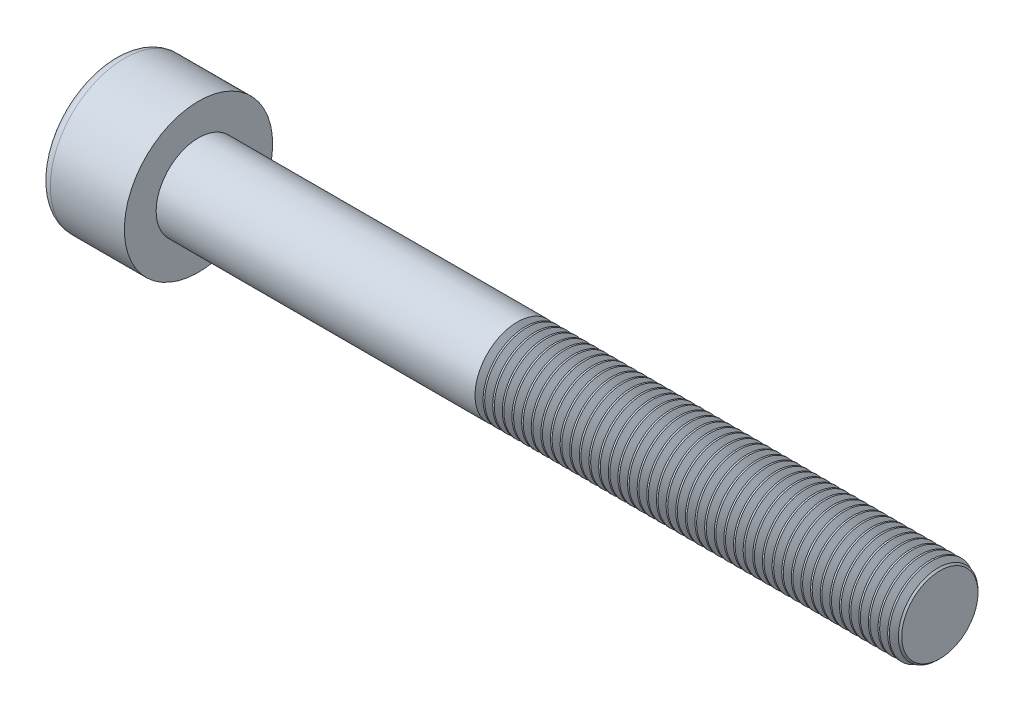
SolidWorks part; units mm, degrees
ref_plane "Front" through (0, 0, 0) normal (0, 0, 1) x (1, 0, 0)
ref_plane "Top" through (0, 0, 0) normal (0, 1, 0) x (1, 0, 0)
ref_plane "Right" through (0, 0, 0) normal (1, 0, 0) x (0, 0, -1)
sketch "Sketch1" plane through (0, 0, 0) normal (1, 0, 0) x (0, 0, -1)
  circle A0 centre (0, 0) radius 3.5
  dimension "dk" = 7
extrude "BaseHead" add sketch "Sketch1" along normal blind 4
sketch "Sketch2" plane through (4, 0, 0) normal (1, 0, 0) x (0, 0, -1)
  circle A0 centre (0, 0) radius 2
  dimension "d" = 4
extrude "BaseBody" add sketch "Sketch2" along normal blind 35
cosmetic thread "ThreadCosmetic1" [suppressed] parameters "b"=20, "D2"=3.242
sketch "Sketch3" plane through (0, 0, 0) normal (1, 0, 0) x (0, 0, -1)
  line L1 (1.7321, 0) -> (0.866, 1.5)
  line L2 (0.866, 1.5) -> (-0.866, 1.5)
  line L3 (-0.866, 1.5) -> (-1.7321, 0)
  line L4 (-1.7321, 0) -> (-0.866, -1.5)
  line L5 (-0.866, -1.5) -> (0.866, -1.5)
  line L6 (0.866, -1.5) -> (1.7321, 0)
  circle A0 centre (0, 0) radius 1.5 construction
  dimension "s" = 3
  dimension "e" = 3.4641
extrude "HexagonSocket" cut sketch "Sketch3" along normal blind 2
sketch "Sketch4" plane through (-4.1961, 0.75, 0) normal (0, 0, 1) x (-1, 0, 0)
  line L0 (-6.1961, 2.25) -> (-7.0622, 0.75)
  line L2 (-7.0622, 0.75) -> (-6.1961, 0.75)
  line L3 (-6.1961, 0.75) -> (-6.1961, 2.25)
  line L4 (-5.0351, 0.75) -> (0.839, 0.75) construction
  line L5 (-43.1961, 0.75) -> (-8.1961, 0.75) construction
  line L6 (-8.1961, 0.75) -> (-4.1961, 0.75) construction
  dimension "m" = 60
revolve "Cut-Revolve1" cut sketch "Sketch4" angle 360 about L4
fillet "HeadFillet" [suppressed] radius 0.2
fillet "TopFillet" radius 0.5 1 edges at (0, 0, -3.5)
chamfer "Chamfer1" distance 0.2 angle 45 1 edges at (39, 0, -2)
sketch "Sketch5" plane through (0, 0, 0) normal (0, 0, 1) x (1, 0, 0)
  line L0 (38.8, 1.6718) -> (38.9895, 2)
  line L1 (38.9895, 2) -> (38.9895, 2.379)
  line L2 (38.9895, 2.379) -> (38.6105, 2.379)
  line L3 (38.6105, 2.379) -> (38.6105, 2)
  line L4 (38.6105, 2) -> (38.8, 1.6718)
  line L5 (0, 0) -> (7.8886, 0) construction
  line L6 (38.8, -2) -> (38.8, 2) construction
  dimension "D1" = 4
  dimension "D2" = 0.379
revolve "Cut-Revolve10" cut sketch "Sketch5" angle 360 about L5
pattern_linear "LPattern10" count 44 spacing 0.4548 along (-1, 0, 0) of "Cut-Revolve10"
equation "\"r1@TopFillet\" = \"d@Sketch2\" / 8"
equation "\"D1@Chamfer1\" = \"r@HeadFillet\""
equation "\"D1@Sketch5\" = \"d@Sketch2\""
equation "\"D2@Sketch5\" =  ( \"d@Sketch2\" - \"D2@ThreadCosmetic1\" )  / 2"
equation "\"D3@LPattern10\" = \"D2@Sketch5\" * 1.2"
equation "\"D1@LPattern10\" = \"b@ThreadCosmetic1\" / \"D3@LPattern10\""
